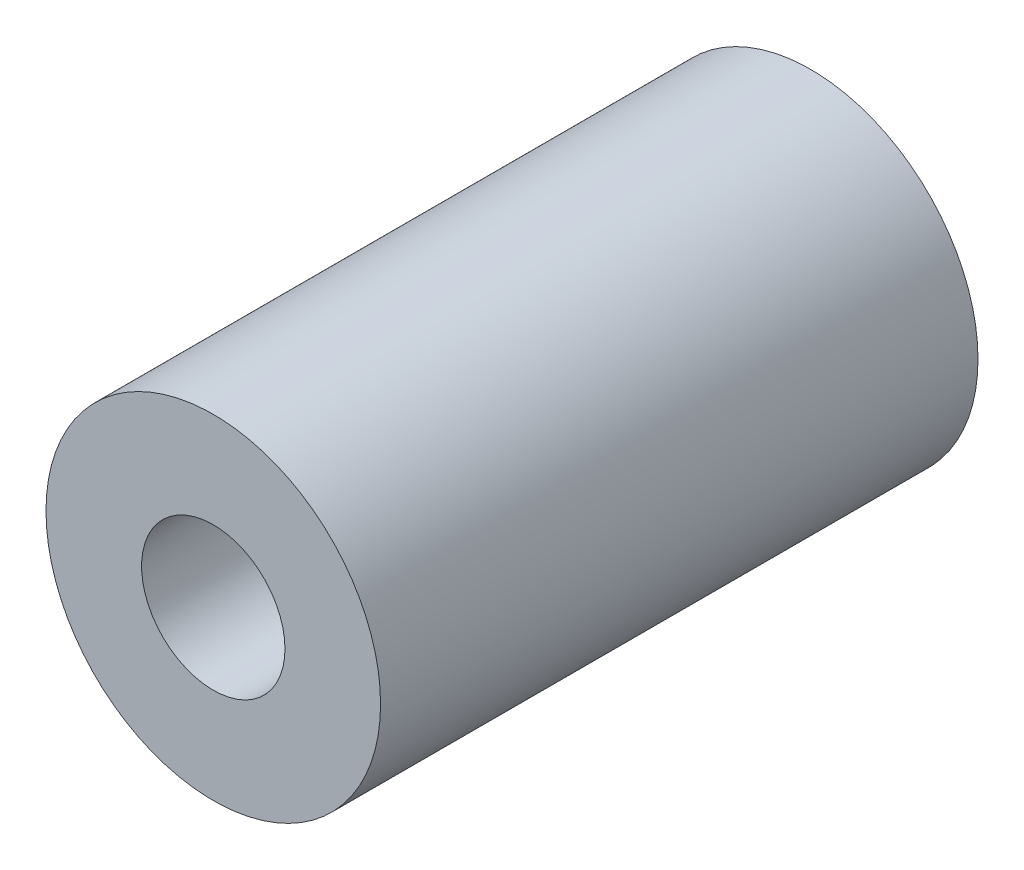
SolidWorks part; units mm, degrees
ref_plane "Front Plane" through (0, 0, 0) normal (0, 0, 1) x (1, 0, 0)
ref_plane "Top Plane" through (0, 0, 0) normal (0, 1, 0) x (1, 0, 0)
ref_plane "Right Plane" through (0, 0, 0) normal (1, 0, 0) x (0, 0, -1)
sketch "Sketch1" plane through (0, 0, 0) normal (0, 0, 1) x (1, 0, 0)
  circle A0 centre (0, 0) radius 7
  circle A1 centre (0, 0) radius 3
  dimension "D1" = 6
  dimension "D2" = 14
extrude "Boss-Extrude1" add sketch "Sketch1" along normal blind 25
